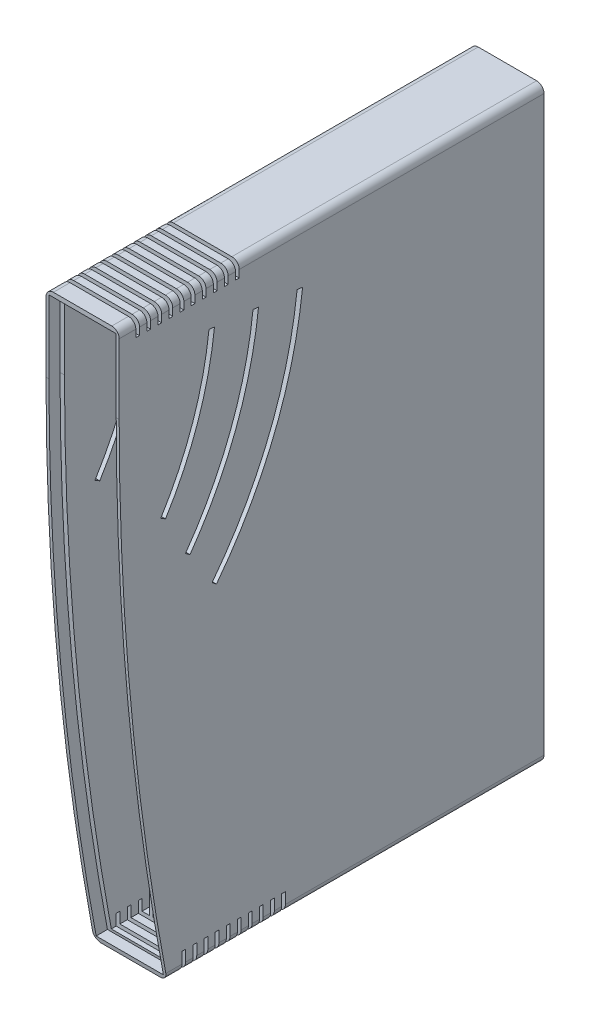
SolidWorks part; units mm, degrees
ref_plane "Front Plane" through (0, 0, 0) normal (0, 0, 1) x (1, 0, 0)
ref_plane "Top Plane" through (0, 0, 0) normal (0, 1, 0) x (1, 0, 0)
ref_plane "Right Plane" through (0, 0, 0) normal (1, 0, 0) x (0, 0, -1)
sketch "Sketch1" plane through (0, 0, 0) normal (0, 0, 1) x (1, 0, 0)
  line L1 (-9.905, -79.55) -> (9.905, -79.55)
  line L2 (-9.905, -79.55) -> (-9.905, 79.55)
  line L3 (-9.905, 79.55) -> (9.905, 79.55)
  line L4 (9.905, -79.55) -> (9.905, 79.55)
  line L5 (-9.905, -79.55) -> (9.905, 79.55) construction
  line L6 (-9.905, 79.55) -> (9.905, -79.55) construction
  point P0 (0, 0)
  dimension "D1" = 19.81
  dimension "D2" = 159.1
extrude "Boss-Extrude1" add sketch "Sketch1" along normal blind 115
shell "Shell1" thickness 2
sketch "Sketch2" plane through (9.905, 0, 0) normal (1, 0, 0) x (0, 0, -1)
  line L2 (-115, 79.55) -> (-115, 58.65)
  line L3 (-115, -79.55) -> (-115, 79.55) construction
  line L4 (-115, -79.55) -> (0, -79.55) construction
  arc A0 (-115, 58.65) -> (-102, -79.55) centre (626.0862, 58.65) ccw
  dimension "D1" = 20.9
  dimension "D2" = 13
extrude "Cut-Extrude1" cut sketch "Sketch2" along normal through all and the other way through all flip side to cut
fillet "Fillet1" radius 2 4 edges at (-9.905, -79.55, 51) (9.905, -79.55, 51) (-9.905, 79.55, 57.5) (9.905, 79.55, 57.5)
sketch "Sketch3" plane through (0, 79.55, 0) normal (0, 1, 0) x (1, 0, 0)
  line L0 (7.905, -115) -> (-7.905, -115) construction
  line L1 (-10.5, -109.5) -> (10.5, -109.5)
  line L2 (-10.5, -109.5) -> (-10.5, -110.5)
  line L3 (-10.5, -110.5) -> (10.5, -110.5)
  line L4 (10.5, -109.5) -> (10.5, -110.5)
  line L5 (-10.5, -109.5) -> (10.5, -110.5) construction
  line L6 (-10.5, -110.5) -> (10.5, -109.5) construction
  line L7 (0, -115) -> (0, -105.7345) construction
  point P0 (0, -110)
  dimension "D1" = 1
  dimension "D2" = 5
  dimension "D3" = 21
extrude "Cut-Extrude2" cut sketch "Sketch3" against normal blind 4
pattern_linear "LPattern1" count 10 spacing 3 along (0, 0, -1) of "Cut-Extrude2"
sketch "Sketch8" plane through (0, -79.55, 0) normal (0, -1, 0) x (1, 0, 0)
  line L0 (-7.905, 102) -> (7.905, 102) construction
  line L1 (-13.3258, 98) -> (14.3742, 98)
  line L2 (-13.3258, 98) -> (-13.3258, 97)
  line L3 (-13.3258, 97) -> (14.3742, 97)
  line L4 (14.3742, 98) -> (14.3742, 97)
  dimension "D1" = 4
  dimension "D2" = 1
extrude "Cut-Extrude4" cut sketch "Sketch8" against normal blind 5
pattern_linear "LPattern2" count 10 spacing 3 along (0, 0, -1) of "Cut-Extrude4"
sketch "Sketch5" plane through (-9.905, 0, 0) normal (-1, 0, 0) x (0, 0, 1)
  line L0 (65.347, 64.8235) -> (66.8382, 64.9865)
  line L1 (77.276, 66.1274) -> (78.7671, 66.2904)
  line L2 (89.2049, 67.4313) -> (90.6961, 67.5942)
  line L3 (88.6672, 6.884) -> (89.8554, 7.7995)
  line L5 (95.8273, 17.3757) -> (97.0496, 18.2452)
  line L6 (102.4576, 29.0608) -> (103.7315, 29.8528)
  arc A0 (90.6961, 67.5942) -> (103.7315, 29.8528) centre (180.1632, 77.3732) ccw
  arc A1 (89.2049, 67.4313) -> (102.4576, 29.0608) centre (180.1632, 77.3732) ccw
  arc A2 (77.276, 66.1274) -> (95.8273, 17.3757) centre (180.1632, 77.3732) ccw
  arc A3 (78.7671, 66.2904) -> (97.0496, 18.2452) centre (180.1632, 77.3732) ccw
  arc A4 (66.8382, 64.9865) -> (89.8554, 7.7995) centre (180.1632, 77.3732) ccw
  arc A5 (65.347, 64.8235) -> (88.6672, 6.884) centre (180.1632, 77.3732) ccw
  arc A6 (90.6961, 67.5942) -> (108.8676, 22.4466) centre (180.1632, 77.3732) ccw construction
  arc A7 (89.2049, 67.4313) -> (107.6794, 21.5311) centre (180.1632, 77.3732) ccw construction
  arc A8 (78.7671, 66.2904) -> (99.3615, 15.123) centre (180.1632, 77.3732) ccw construction
  arc A9 (77.276, 66.1274) -> (98.1733, 14.2076) centre (180.1632, 77.3732) ccw construction
  dimension "D6" = 90
  dimension "D4" = 12
  dimension "D1" = 1.5
  dimension "D2" = 12
  dimension "D3" = 1.5
  dimension "D5" = 1.5
extrude "Cut-Extrude3" cut sketch "Sketch5" against normal through all
ref_plane "Plane1" through (0, 0, 95) normal (0, 0, 1) x (1, 0, 0)
sketch "Sketch7" plane through (0, 0, 95) normal (0, 0, 1) x (1, 0, 0)
  line L0 (-5.905, 77.55) -> (-5.905, 71.05)
  line L1 (-5.905, 71.05) -> (-4.905, 71.05)
  line L2 (-4.905, 71.05) -> (-4.905, 77.55)
  line L3 (-4.905, 77.55) -> (-5.905, 77.55)
  line L4 (-3.105, 77.55) -> (-3.105, 71.05)
  line L5 (7.905, 77.55) -> (-7.905, 77.55) construction
  line L6 (-3.105, 71.05) -> (-2.105, 71.05)
  line L7 (-2.105, 71.05) -> (-2.105, 77.55)
  line L8 (-2.105, 77.55) -> (-3.105, 77.55)
  line L9 (-7.905, 77.55) -> (-7.905, -77.55) construction
  dimension "D1" = 3
  dimension "D2" = 1
  dimension "D3" = 1.8
  dimension "D4" = 6.5
  dimension "D5" = 1
extrude "Boss-Extrude3" add sketch "Sketch7" against normal blind 90
chamfer "Chamfer2" distance 0.5 angle 45 2 edges at (-3.105, 74.3, 95) (-4.905, 74.3, 95)
sketch "Sketch10" plane through (0, 0, 0) normal (1, 0, 0) x (0, 0, -1)
  line L1 (-131.7092, 78.35) -> (-112, 78.35)
  line L2 (-112, 58.65) -> (-112, 77.55)
  line L3 (-112, 58.65) -> (-112, 78.35)
  line L4 (-110.5, 77.55) -> (-115, 77.55) construction
  line L5 (-102.9238, -78.35) -> (-99.1739, -78.35)
  line L6 (-102.3768, -77.55) -> (-98, -77.55) construction
  line L7 (-131.7092, 78.35) -> (-102.9238, -78.35)
  arc A3 (-112, 58.65) -> (-99.4279, -76.9986) centre (626.0862, 58.65) ccw
  arc A4 (-112, 58.65) -> (-99.1739, -78.35) centre (626.0862, 58.65) ccw
  dimension "D2" = 0.8
  dimension "D3" = 0.8
  dimension "D1" = 3
extrude "Cut-Extrude6" cut sketch "Sketch10" against normal mid plane 18.21
sketch "Sketch11" plane through (0, 0, 2) normal (0, 0, 1) x (1, 0, 0)
  line L0 (7.905, -77.55) -> (-7.905, -77.55) construction
  line L1 (-5.905, -77.55) -> (-4.905, -77.55)
  line L2 (-5.905, -77.55) -> (-5.905, -71.05)
  line L3 (-5.905, -71.05) -> (-4.905, -71.05)
  line L4 (-4.905, -77.55) -> (-4.905, -71.05)
  line L5 (-7.905, -77.55) -> (7.905, -77.55) construction
  line L6 (-3.105, -77.55) -> (-2.105, -77.55)
  line L7 (-3.105, -77.55) -> (-3.105, -71.05)
  line L8 (-3.105, -71.05) -> (-2.105, -71.05)
  line L9 (-2.105, -77.55) -> (-2.105, -71.05)
  line L10 (-7.905, 77.55) -> (-7.905, -77.55) construction
  dimension "D1" = 6.5
  dimension "D2" = 6.5
  dimension "D3" = 3
  dimension "D4" = 1
  dimension "D5" = 1.8
  dimension "D6" = 1
extrude "Boss-Extrude6" add sketch "Sketch11" along normal blind 89
